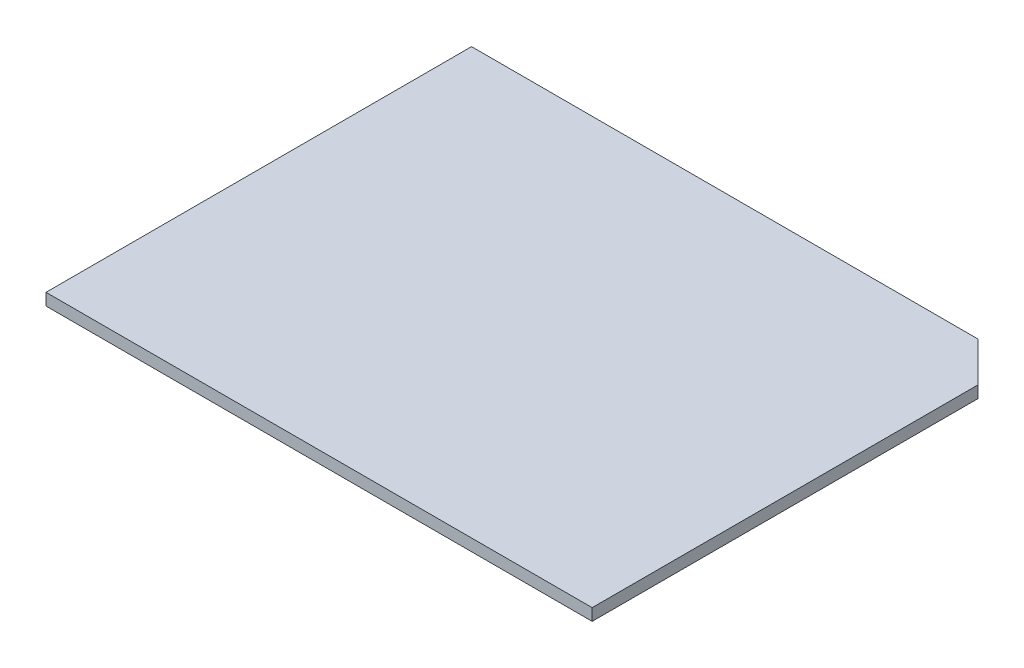
SolidWorks part; units mm, degrees
ref_plane "Front Plane" through (0, 0, 0) normal (0, 0, 1) x (1, 0, 0)
ref_plane "Top Plane" through (0, 0, 0) normal (0, 1, 0) x (1, 0, 0)
ref_plane "Right Plane" through (0, 0, 0) normal (1, 0, 0) x (0, 0, -1)
sketch "Sketch1" plane through (0, 0, 0) normal (0, 1, 0) x (1, 0, 0)
  line L0 (-58.6489, 9.632) -> (-58.6489, -43.958)
  line L1 (-58.6489, -43.958) -> (10.1311, -43.958)
  line L2 (10.1311, -43.958) -> (10.1311, 4.632)
  line L3 (5.1311, 9.632) -> (-58.6489, 9.632)
  line L4 (10.1311, 4.632) -> (5.1311, 9.632)
  point P4 (10.1311, 9.632)
  dimension "D1" = 53.59
  dimension "D2" = 68.78
extrude "Boss-Extrude1" add sketch "Sketch1" along normal blind 1.5
